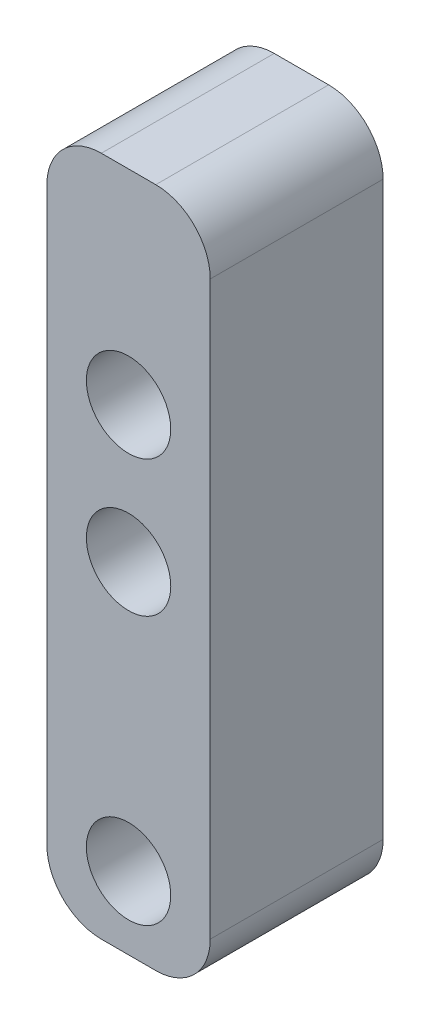
SolidWorks part; units mm, degrees
ref_plane "Plan de face" through (0, 0, 0) normal (0, 0, 1) x (1, 0, 0)
ref_plane "Plan de dessus" through (0, 0, 0) normal (0, 1, 0) x (1, 0, 0)
ref_plane "Plan de droite" through (0, 0, 0) normal (1, 0, 0) x (0, 0, -1)
sketch "Esquisse1" plane through (0, 0, 0) normal (0, 0, 1) x (1, 0, 0)
  line L0 (-5, 0) -> (49995, 0) construction
  line L1 (-3, -12.5) -> (3, -12.5)
  line L2 (-3, -12.5) -> (-3, 12.5)
  line L3 (-3, 12.5) -> (3, 12.5)
  line L4 (3, -12.5) -> (3, 12.5)
  line L5 (-3, -12.5) -> (3, 12.5) construction
  line L6 (-3, 12.5) -> (3, -12.5) construction
  line L7 (0, -12.5) -> (0, 49987.5) construction
  circle A1 centre (0, -9.8379) radius 1.55
  circle A2 centre (0, 0) radius 1.55
  circle A3 centre (0, 5) radius 1.55
  point P0 (0, 0)
  point P10 (-3, 0)
  point P15 (1.4258, 4.6226)
  point P18 (0, -12.5)
  point P19 (1.3457, 9.9519)
  point P20 (0, 1.6401)
  point P21 (0, 9.1112)
  point P22 (0, -9.8379)
  point P23 (-0.3272, 1.3634)
  dimension "D3" = 3.1
  dimension "D4" = 3.1
  dimension "D1" = 25
  dimension "D2" = 6
  dimension "D5" = 5
extrude "Boss.-Extru.1" add sketch "Esquisse1" along normal blind 6.35
fillet "Congé1" radius 2 4 edges at (3, -12.5, 3.175) (-3, -12.5, 3.175) (-3, 12.5, 3.175) (3, 12.5, 3.175)
